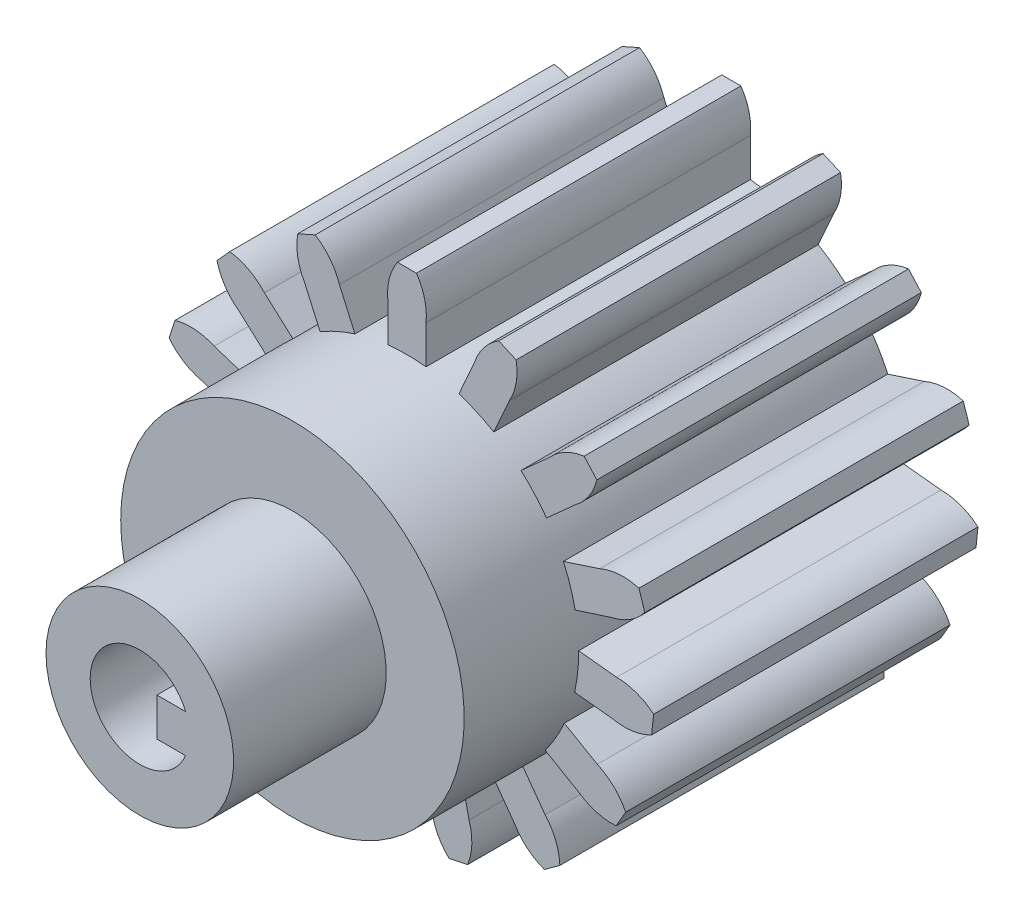
SolidWorks part; units mm, degrees
other "Markup1"
sketch "Sketch16" plane through (-12.9256, -12.7654, 5) normal (-0.0162, -0.0045, -0.9999) x (-0.9979, -0.0628, 0.0165)
ref_plane "Front Plane" through (0, 0, 0) normal (0, 0, 1) x (1, 0, 0)
ref_plane "Top Plane" through (0, 0, 0) normal (0, 1, 0) x (1, 0, 0)
ref_plane "Right Plane" through (0, 0, 0) normal (1, 0, 0) x (0, 0, -1)
sketch "Sketch1" plane through (0, 0, 0) normal (0, 0, 1) x (1, 0, 0)
  circle A0 centre (0, 0) radius 9
  circle A1 centre (0, 0) radius 2.6
  dimension "D1" = 5.2
  dimension "D2" = 18
extrude "Boss-Extrude1" add sketch "Sketch1" along normal blind 36
sketch "Sketch5" plane through (0, 0, 0) normal (1, 0, 0) x (0, 0, -1)
  line L0 (0, 0) -> (-30, 0) construction
  line L1 (-36, 9) -> (-36, -9) construction
  line L2 (-30, 0) -> (-15, 0) construction
  line L4 (-5, 4.915) -> (-5, 9)
  line L5 (0, 9) -> (-36, 9) construction
  line L6 (-36, 4.915) -> (-28, 4.915)
  line L7 (-36, 4.915) -> (-36, 9)
  line L8 (-36, 9) -> (-28, 9)
  line L9 (-28, 4.915) -> (-28, 9)
  line L10 (0, 9) -> (-5, 9)
  line L11 (0, 4.915) -> (0, 9)
  line L12 (0, 4.915) -> (-5, 4.915)
  dimension "D1" = 5
  dimension "D2" = 8
revolve "Cut-Revolve1" cut sketch "Sketch5" angle 360 about L0
sketch "Sketch6" plane through (0, 0, 0) normal (0, 0, 1) x (1, 0, 0)
  line L0 (0, 0) -> (0, 9) construction
  line L1 (-1, 8.9443) -> (-1, 10.9443)
  line L2 (-1, 8.9443) -> (1, 8.9443)
  line L3 (1, 10.9443) -> (1, 8.9443)
  line L7 (-0.5, 12.9443) -> (0.5, 12.9443)
  circle A0 centre (0, 0) radius 9 construction
  arc A1 (-1, 10.9443) -> (-0.5, 12.9443) centre (1.9832, 11.261) cw
  arc A2 (1, 10.9443) -> (0.5, 12.9443) centre (-1.9832, 11.261) ccw
  dimension "D7" = 3
  dimension "D8" = 3
  dimension "D2" = 1
  dimension "D3" = 2
  dimension "D6" = 2
extrude "Boss-Extrude2" add sketch "Sketch6" along normal blind 22
sketch "Sketch7" plane through (0, 0, 0) normal (1, 0, 0) x (0, 0, -1)
  line L0 (0, 0) -> (-5, -0.0279) construction
  line L1 (-5, -9) -> (-5, 8.9443) construction
  line L2 (-5, -0.0279) -> (-5, 15.9143) construction
  line L3 (0, 8.9443) -> (0, 10.9443) construction
  line L4 (-5, 8.9443) -> (0, 8.9443)
  line L5 (-5, 8.9443) -> (-5, 13.5982)
  line L6 (-5, 13.5982) -> (0, 13.5982)
  line L7 (0, 8.9443) -> (0, 13.5982)
  line L8 (-5, 8.9443) -> (0, 8.9443) construction
  dimension "D1" = 5
revolve "Cut-Revolve2" cut sketch "Sketch7" angle 90 about L4 other way angle 90
pattern_circular "CirPattern1" count 15 over 360 about axis through (0, 0, 0) along (0, 0, 1) of "Boss-Extrude2"
sketch "Sketch13" plane through (0, 0, 0) normal (1, 0, 0) x (0, 0, -1)
  line L0 (-25.5784, 0) -> (2.5167, 0) construction
  line L1 (-5, 16.6164) -> (0, 16.6164)
  line L2 (-5, 16.6164) -> (-5, 0)
  line L3 (-5, 0) -> (0, 0)
  line L4 (0, 16.6164) -> (0, 0)
  dimension "D1" = 5
revolve "Cut-Revolve6" cut sketch "Sketch13" angle 360 about L0
sketch "Sketch14" plane through (0, 0, 5) normal (0, 0, -1) x (-1, 0, 0)
  circle A0 centre (0, 0) radius 10.0936
ref_plane "Plane1" through (0, 0, 13.5) normal (0, 0, -1) x (-1, 0, 0)
sketch "Sketch15" plane through (0, 0, 13.5) normal (0, 0, -1) x (-1, 0, 0)
  circle A0 centre (0, 0) radius 9.3981
sketch "Sketch17" plane through (0, 0, 0) normal (0, 1, 0) x (1, 0, 0)
  circle A0 centre (-0.1287, -25.1112) radius 2
  dimension "D1" = 4
extrude "Cut-Extrude1" cut sketch "Sketch17" against normal blind 10
sketch "Sketch19" plane through (0, 0, 36) normal (0, 0, 1) x (1, 0, 0)
  line L0 (0, 0) -> (4.1068, 0) construction
  line L1 (2.4, 1) -> (3.9, 1)
  line L2 (3.9, 1) -> (3.9, -1)
  line L3 (3.9, -1) -> (2.4, -1)
  line L5 (2.4, 1) -> (0.9, 1)
  line L6 (0.9, 1) -> (0.9, -1)
  line L7 (0.9, -1) -> (2.4, -1)
  circle A0 centre (0, 0) radius 2.6 construction
  point P7 (2.3908, -1)
  dimension "D1" = 2
  dimension "D2" = 1.5
extrude "Boss-Extrude3" add sketch "Sketch19" against normal up to surface (31 mm away)
